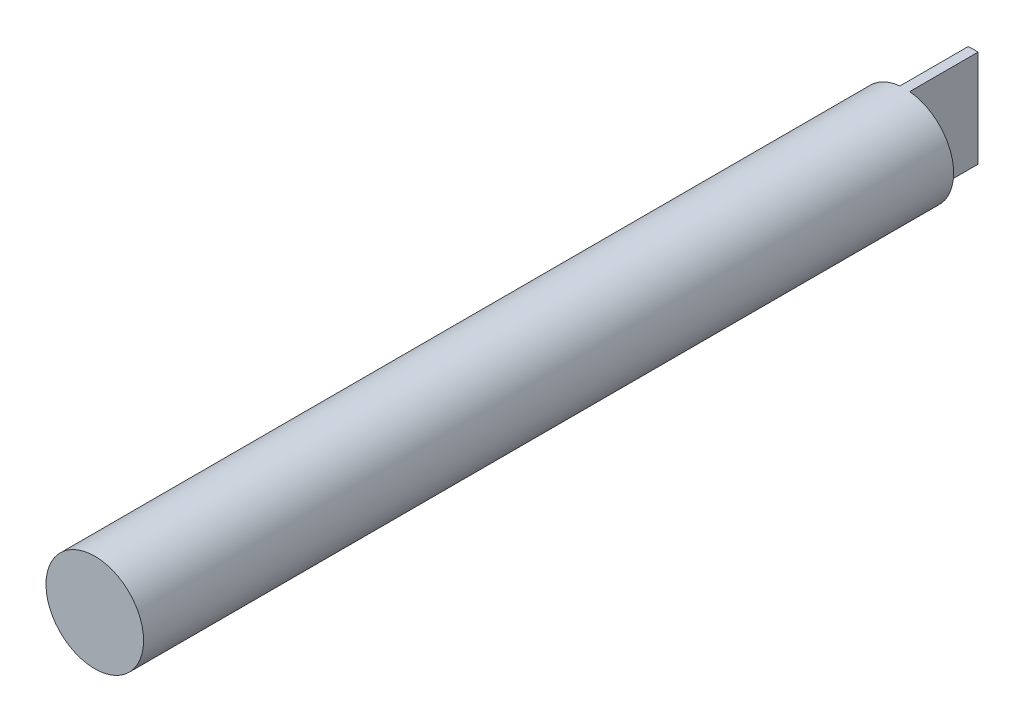
SolidWorks part; units mm, degrees
material "AISI 1020"
ref_plane "Plano frontal" through (0, 0, 0) normal (0, 0, 1) x (1, 0, 0)
ref_plane "Plano superior" through (0, 0, 0) normal (0, 1, 0) x (1, 0, 0)
ref_plane "Plano direito" through (0, 0, 0) normal (1, 0, 0) x (0, 0, -1)
sketch "Esboço1" plane through (0, 0, 0) normal (0, 0, 1) x (1, 0, 0)
  circle A0 centre (208.8814, 100) radius 5
  dimension "D1" = 10
extrude "Ressalto-extrusão1" add sketch "Esboço1" along normal mid plane 90
sketch "Sketch2" plane through (0, 0, -45) normal (0, 0, -1) x (-1, 0, 0)
  line L0 (-208.8814, 105) -> (-208.8814, 95) construction
  line L1 (-208.3814, 105) -> (-208.3814, 95)
  line L2 (-214.3814, 105) -> (-209.3814, 105)
  line L3 (-214.3814, 105) -> (-214.3814, 95)
  line L4 (-214.3814, 95) -> (-209.3814, 95)
  line L5 (-209.3814, 105) -> (-209.3814, 95)
  line L6 (-203.3814, 95) -> (-208.3814, 95)
  line L7 (-203.3814, 105) -> (-203.3814, 95)
  line L8 (-203.3814, 105) -> (-208.3814, 105)
  circle A0 centre (-208.8814, 100) radius 5 construction
  point P9 (-208.8814, 100)
  dimension "D1" = 5
  dimension "D2" = 10
  dimension "D3" = 5
  dimension "D4" = 1
extrude "Cut-Extrude2" cut sketch "Sketch2" against normal blind 7
